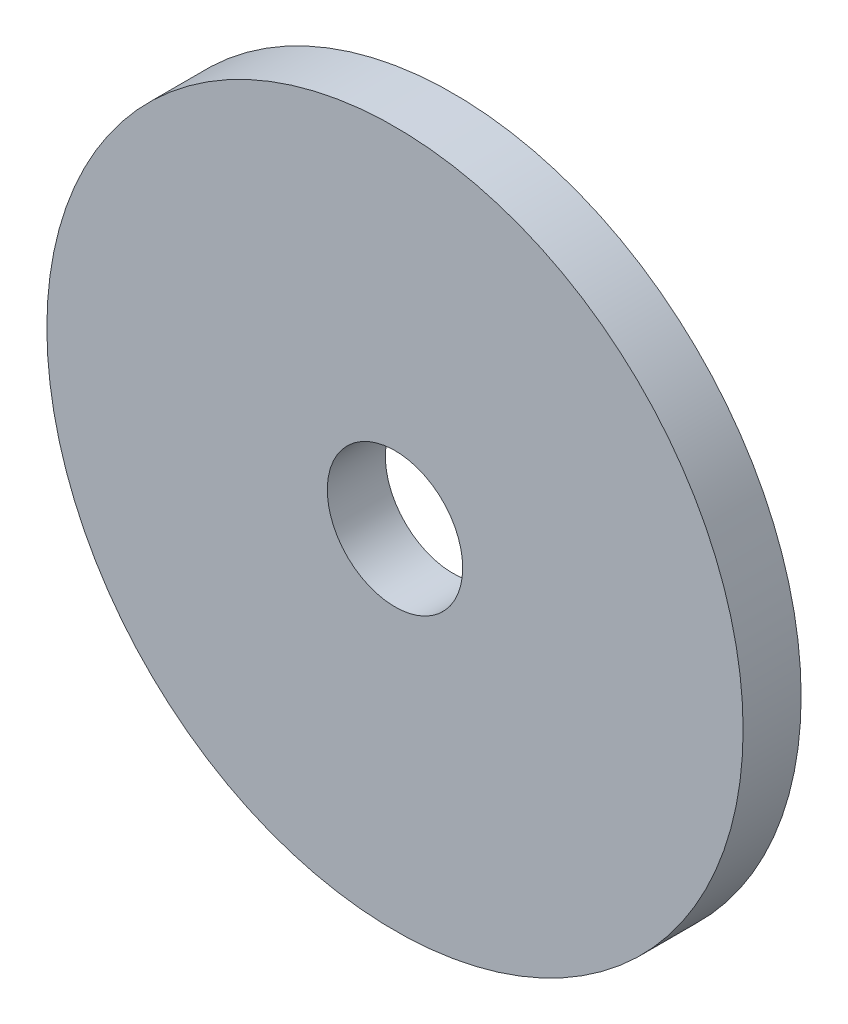
SolidWorks part; units mm, degrees
ref_plane "Front Plane" through (0, 0, 0) normal (0, 0, 1) x (1, 0, 0)
ref_plane "Top Plane" through (0, 0, 0) normal (0, 1, 0) x (1, 0, 0)
ref_plane "Right Plane" through (0, 0, 0) normal (1, 0, 0) x (0, 0, -1)
sketch "Sketch1" plane through (0, 0, 0) normal (0, 0, 1) x (1, 0, 0)
  circle A0 centre (0, 0) radius 228.6
  dimension "D1" = 457.2
extrude "Boss-Extrude1" add sketch "Sketch1" along normal blind 38.1
sketch "Sketch2" plane through (0, 0, 38.1) normal (0, 0, 1) x (1, 0, 0)
  circle A0 centre (0, 0) radius 44.45
  dimension "D1" = 88.9
extrude "Cut-Extrude1" cut sketch "Sketch2" against normal blind 38.1 contours A0
